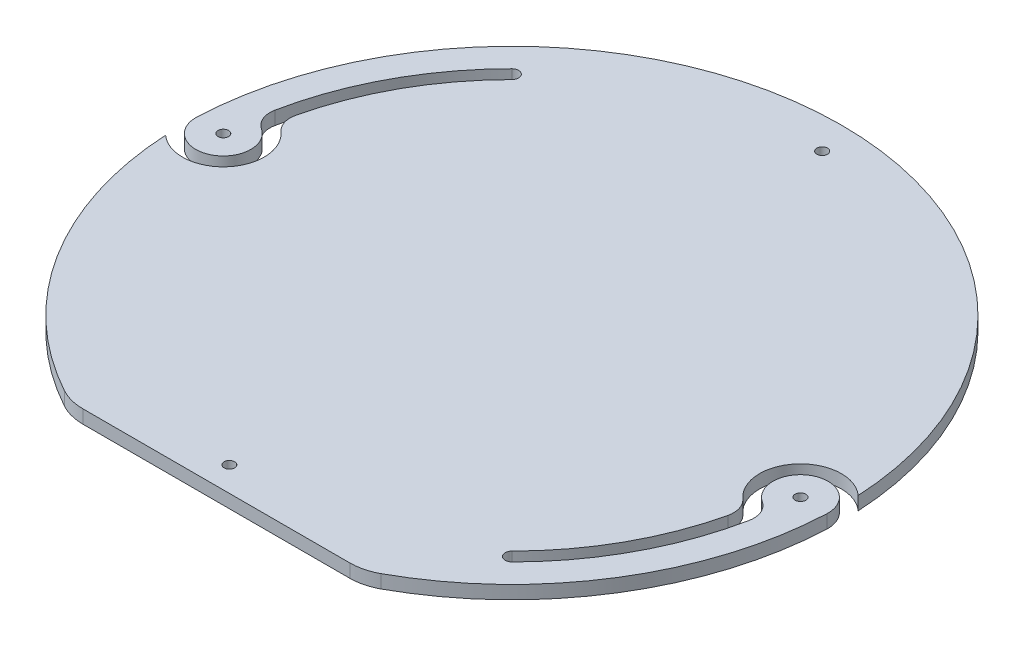
SolidWorks part; units mm, degrees
material "ABS"
ref_plane "Front Plane" through (0, 0, 0) normal (0, 0, 1) x (1, 0, 0)
ref_plane "Top Plane" through (0, 0, 0) normal (0, 1, 0) x (1, 0, 0)
ref_plane "Right Plane" through (0, 0, 0) normal (1, 0, 0) x (0, 0, -1)
sketch "Sketch1" plane through (0, 0, 0) normal (0, 1, 0) x (1, 0, 0)
  line L0 (-30.03, -64.8129) -> (30.03, -64.8129) construction
  line L1 (0, -85) -> (0, 0) construction
  line L2 (0, -85) -> (32.4891, -64.8129) construction
  line L3 (-30.03, -66.5129) -> (30.03, -66.5129)
  arc A0 (34.8348, -63.5829) -> (-34.8348, -63.5829) centre (0, 0) ccw construction
  circle A1 centre (0, -85) radius 38.25 construction
  arc A2 (30.03, -64.8129) -> (34.8348, -63.5829) centre (30.03, -54.8129) ccw construction
  arc A3 (-30.03, -64.8129) -> (-34.8348, -63.5829) centre (-30.03, -54.8129) cw construction
  arc A4 (35.6516, -65.0738) -> (-35.6516, -65.0738) centre (0, 0) ccw
  arc A5 (-30.03, -66.5129) -> (-35.6516, -65.0738) centre (-30.03, -54.8129) cw
  arc A6 (30.03, -66.5129) -> (35.6516, -65.0738) centre (30.03, -54.8129) ccw
  dimension "D1" = 145
  dimension "D2" = 76.5
  dimension "D4" = 10
  dimension "D3" = 85
  dimension "D5" = 1.7
extrude "Boss-Extrude1" add sketch "Sketch1" along normal blind 3
sketch "Sketch2" plane through (0, 3, 0) normal (0, 1, 0) x (1, 0, 0)
  line L0 (0, 0) -> (2.9225, 66.9362) construction
  line L1 (0, 0) -> (-2.6608, -60.9419) construction
  line L2 (0, 0) -> (-67.9353, 2.9661) construction
  line L3 (0, 0) -> (67.9353, -2.9661) construction
  line L4 (0, 0) -> (0, -66.5129) construction
  line L5 (-30.03, -66.5129) -> (30.03, -66.5129) construction
  circle A0 centre (-2.6608, -60.9419) radius 1.2
  circle A1 centre (-67.9353, 2.9661) radius 1.2
  circle A2 centre (2.9225, 66.9362) radius 1.2
  circle A3 centre (67.9353, -2.9661) radius 1.2
  dimension "D4" = 2.4
  dimension "D1" = 67
  dimension "D2" = 61
  dimension "D3" = 2.5
  dimension "D5" = 68
extrude "Cut-Extrude1" cut sketch "Sketch2" against normal through all
sketch "Sketch3" plane through (0, 3, 0) normal (0, 1, 0) x (1, 0, 0)
  line L0 (-48.0833, 48.0833) -> (-45.9619, 45.9619) construction
  line L1 (0, 0) -> (-74.2, 0) construction
  line L2 (-61.7353, 2.9661) -> (-58.7353, 2.9661) construction
  line L3 (48.0833, -48.0833) -> (45.9619, -45.9619) construction
  line L4 (0, 0) -> (74.2, 0) construction
  line L5 (61.7353, -2.9661) -> (58.7353, -2.9661) construction
  arc A0 (-74.1294, 3.2366) -> (-64.5294, 8.1468) centre (-67.9353, 2.9661) ccw
  arc A1 (35.6516, -65.0738) -> (-35.6516, -65.0738) centre (0, 0) ccw construction
  arc A2 (-66.6861, 13.303) -> (-48.0833, 48.0833) centre (0, 0) cw
  arc A3 (-45.9619, 45.9619) -> (-63.3242, 14.6643) centre (0, 0) ccw
  arc A4 (-61.7919, 9.8144) -> (-74.0993, -3.8635) centre (-67.9353, 2.9661) cw
  arc A5 (-74.0993, -3.8635) -> (-74.1294, 3.2366) centre (0, 0) cw
  arc A6 (-45.9619, 45.9619) -> (-48.0833, 48.0833) centre (-47.0226, 47.0226) ccw
  arc A7 (-63.3242, 14.6643) -> (-61.7919, 9.8144) centre (-58.4531, 13.5363) ccw
  arc A8 (-64.5294, 8.1468) -> (-66.6861, 13.303) centre (-61.7827, 12.3248) cw
  arc A9 (74.1294, -3.2366) -> (64.5294, -8.1468) centre (67.9353, -2.9661) ccw
  arc A10 (66.6861, -13.303) -> (48.0833, -48.0833) centre (0, 0) cw
  arc A11 (45.9619, -45.9619) -> (63.3242, -14.6643) centre (0, 0) ccw
  arc A12 (61.7919, -9.8144) -> (74.0993, 3.8635) centre (67.9353, -2.9661) cw
  arc A13 (74.0993, 3.8635) -> (74.1294, -3.2366) centre (0, 0) cw
  arc A14 (45.9619, -45.9619) -> (48.0833, -48.0833) centre (47.0226, -47.0226) ccw
  arc A15 (63.3242, -14.6643) -> (61.7919, -9.8144) centre (58.4531, -13.5363) ccw
  arc A16 (64.5294, -8.1468) -> (66.6861, -13.303) centre (61.7827, -12.3248) cw
  point P39 (0, 0)
  dimension "D3" = 5
  dimension "D1" = 3
  dimension "D2" = 45
  dimension "D4" = 2
extrude "Cut-Extrude2" cut sketch "Sketch3" against normal through all
equation "\"smallPulleyTeeth\"= 30"
equation "\"largePulleyTeeth\"= 30"
equation "\"eighthThick\"= 3.0mm"
equation "\"sixteenthThick\"= 1.7mm"
equation "\"quarterThick\"=6.0mm"
equation "\"OD\"= 145mm"
equation "\"puckAngle\"= 60.5deg"
equation "\"puckDiam\"= 76.5mm"
equation "\"axlePress\"= 5.9mm"
equation "\"press\"= 0.2mm"
equation "\"wheelClear\"= 0.3mm"
equation "\"10-32clear\"= 4.8mm"
equation "\"6-32clear\"= 3.3mm"
equation "\"8-32clear\"= 4.0mm"
equation "\"4-40clear\"= 3.0mm"
equation "\"wheelHeight\"= 22mm"
equation "\"wheelWell\"= 65mm"
equation "\"D1@Sketch1\"=\"OD\""
equation "\"D1@Boss-Extrude1\"=\"eighthThick\""
equation "\"D2@Sketch1\"=\"puckDiam\""
equation "\"puckDist\"= 85mm"
equation "\"scoopFillet\"= 5mm"
equation "\"10-32tap\"= 4.45mm"
equation "\"ledSmall\"= 3.1mm"
equation "\"ledLarge\"= 4.2mm"
equation "\"ledLength\"= 4.2mm"
equation "\"D3@Sketch1\"=\"puckDist\""
equation "\"D5@Sketch1\"=\"sixteenthThick\""
